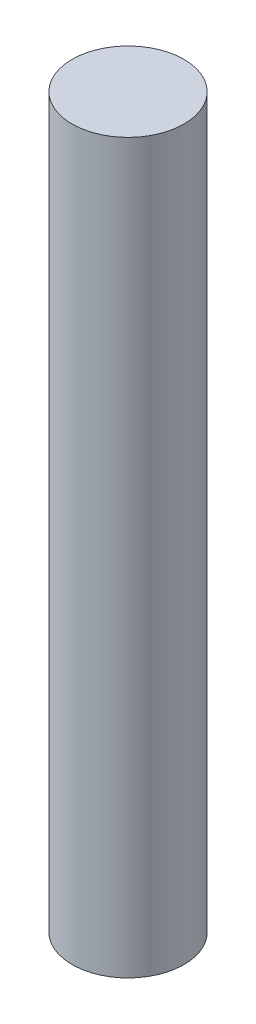
SolidWorks part; units mm, degrees
ref_plane "Front Plane" through (0, 0, 0) normal (0, 0, 1) x (1, 0, 0)
ref_plane "Top Plane" through (0, 0, 0) normal (0, 1, 0) x (1, 0, 0)
ref_plane "Right Plane" through (0, 0, 0) normal (1, 0, 0) x (0, 0, -1)
sketch "Main Body Sketch" plane through (0, 0, 0) normal (0, 1, 0) x (1, 0, 0)
  circle A0 centre (0, 0) radius 1
  dimension "D1" = 2
extrude "Main Body Extrude" add sketch "Main Body Sketch" along normal blind 13
